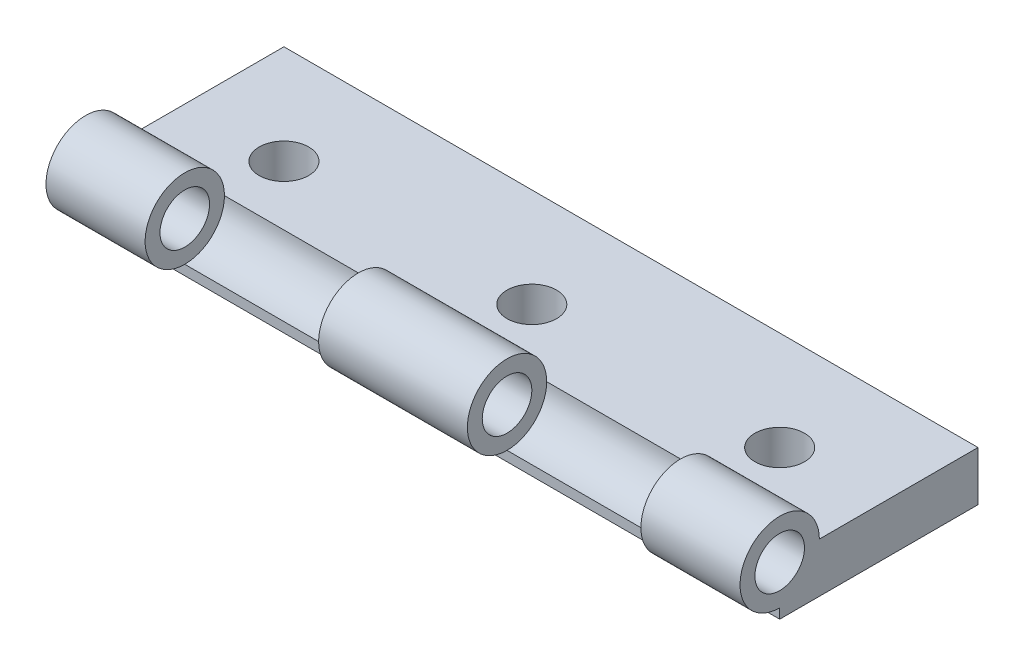
SolidWorks part; units mm, degrees
ref_plane "Front Plane" through (0, 0, 0) normal (0, 0, 1) x (1, 0, 0)
ref_plane "Top Plane" through (0, 0, 0) normal (0, 1, 0) x (1, 0, 0)
ref_plane "Right Plane" through (0, 0, 0) normal (1, 0, 0) x (0, 0, -1)
sketch "Sketch2" plane through (0, 0, 0) normal (0, 1, 0) x (1, 0, 0)
  line L1 (-44.45, 0) -> (44.45, 0)
  line L2 (-44.45, 0) -> (-44.45, 25.4)
  line L3 (-44.45, 25.4) -> (44.45, 25.4)
  line L4 (44.45, 0) -> (44.45, 25.4)
  line L5 (-44.45, 0) -> (44.45, 25.4) construction
  line L6 (-44.45, 25.4) -> (44.45, 0) construction
  circle A0 centre (-31.75, 12.7) radius 3.175
  circle A1 centre (0, 12.7) radius 3.175
  circle A2 centre (31.75, 12.7) radius 3.175
  point P0 (0, 12.7)
  point P12 (31.75, 12.7)
  point P13 (-44.6026, 25.4)
  point P14 (-31.75, 12.7)
  dimension "D5" = 6.35
  dimension "D1" = 25.4
  dimension "D2" = 63.5
  dimension "D3" = 31.75
  dimension "D4" = 88.9
extrude "Boss-Extrude1" add sketch "Sketch2" along normal blind 6.35
sketch "Sketch3" plane through (-44.45, 0, 0) normal (-1, 0, 0) x (0, 0, 1)
  circle A0 centre (0, 6.35) radius 5.08
  dimension "D1" = 10.16
extrude "Cut-Extrude1" cut sketch "Sketch3" against normal through all
sketch "Sketch4" plane through (-44.45, 0, 0) normal (-1, 0, 0) x (0, 0, 1)
  circle A0 centre (0, 6.35) radius 3.175
  arc A2 (-5.08, 6.35) -> (0, 1.27) centre (0, 6.35) ccw construction
  circle A3 centre (0, 6.35) radius 5.08
  dimension "D1" = 6.35
extrude "Boss-Extrude2" add sketch "Sketch4" against normal blind 12.7
mirror "Mirror1" about plane through (0, 0, 0) normal (1, 0, 0) of "Boss-Extrude2"
sketch "Sketch5" plane through (0, 0, 0) normal (1, 0, 0) x (0, 0, -1)
  circle A0 centre (0, 6.35) radius 3.175 construction
  circle A1 centre (0, 6.35) radius 3.175
  circle A2 centre (0, 6.35) radius 5.08
  arc A3 (5.08, 6.35) -> (0, 1.27) centre (0, 6.35) ccw construction
extrude "Boss-Extrude3" add sketch "Sketch5" along normal mid plane 19.05
equation "\"D3@Sketch2\"=\"D2@Sketch2\"/2"
